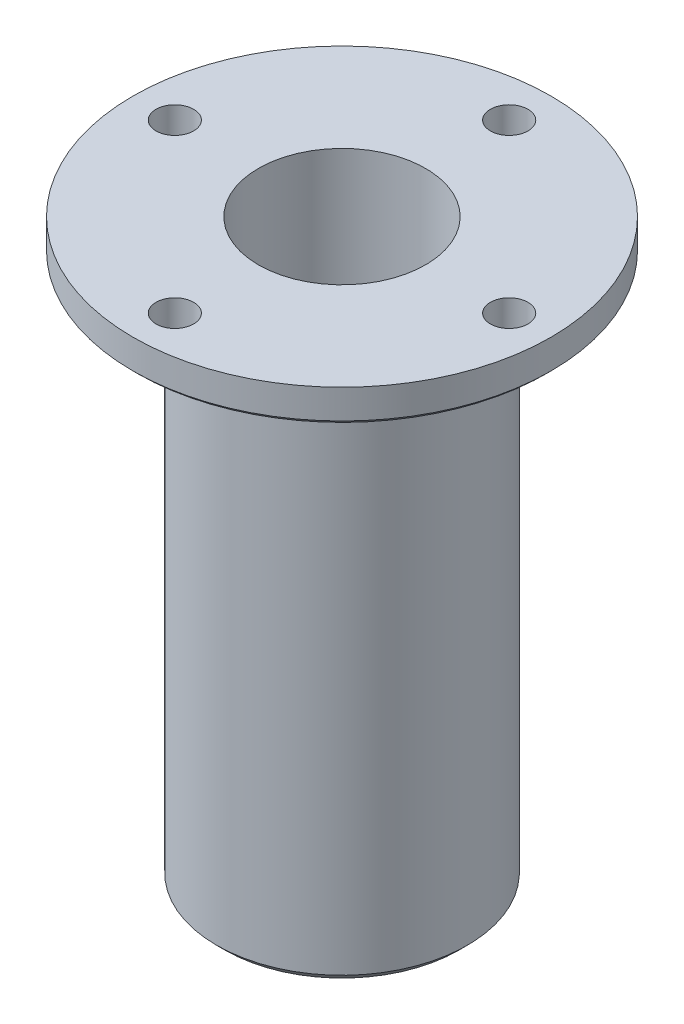
SolidWorks part; units mm, degrees
ref_plane "Front Plane" through (0, 0, 0) normal (0, 0, 1) x (1, 0, 0)
ref_plane "Top Plane" through (0, 0, 0) normal (0, 1, 0) x (1, 0, 0)
ref_plane "Right Plane" through (0, 0, 0) normal (1, 0, 0) x (0, 0, -1)
sketch "Sketch1" plane through (0, 0, 0) normal (0, 1, 0) x (1, 0, 0)
  circle A0 centre (0, 0) radius 10
  circle A1 centre (0, 0) radius 15
  dimension "D1" = 30
  dimension "D2" = 20
extrude "Boss-Extrude1" add sketch "Sketch1" along normal blind 65
sketch "Sketch2" plane through (0, 65, 0) normal (0, 1, 0) x (1, 0, 0)
  circle A0 centre (0, 0) radius 10 construction
  circle A1 centre (0, 0) radius 10
  circle A2 centre (0, 0) radius 20 construction
  circle A3 centre (0, 0) radius 25
  circle A4 centre (20, 0) radius 2.25
  circle A5 centre (0, -20) radius 2.25
  circle A6 centre (-20, 0) radius 2.25
  circle A7 centre (0, 20) radius 2.25
  point P16 (0, 0)
  dimension "D1" = 40
  dimension "D2" = 4.5
  dimension "D3" = 50
  dimension "D4" = 4
extrude "Boss-Extrude2" add sketch "Sketch2" along normal blind 4
sketch "Sketch4" plane through (0, 0, 0) normal (0, -1, 0) x (1, 0, 0)
  circle A0 centre (0, 0) radius 12.5 construction
  circle A1 centre (0, 0) radius 15 construction
  circle A2 centre (12.5, 0) radius 1.4
  circle A3 centre (0, -12.5) radius 1.4
  circle A4 centre (-12.5, 0) radius 1.4
  circle A5 centre (0, 12.5) radius 1.4
  point P16 (0, 0)
  dimension "D1" = 2.5
  dimension "D2" = 2.8
  dimension "D3" = 4
extrude "Cut-Extrude1" cut sketch "Sketch4" against normal blind 20
chamfer "Chamfer1" distance 1 angle 45 1 edges at (0, 0, 15)
chamfer "Chamfer2" distance 0.5 angle 45 1 edges at (0, 65, 25)
fillet "Fillet1" radius 0.5 1 edges at (0, 65, 15)
